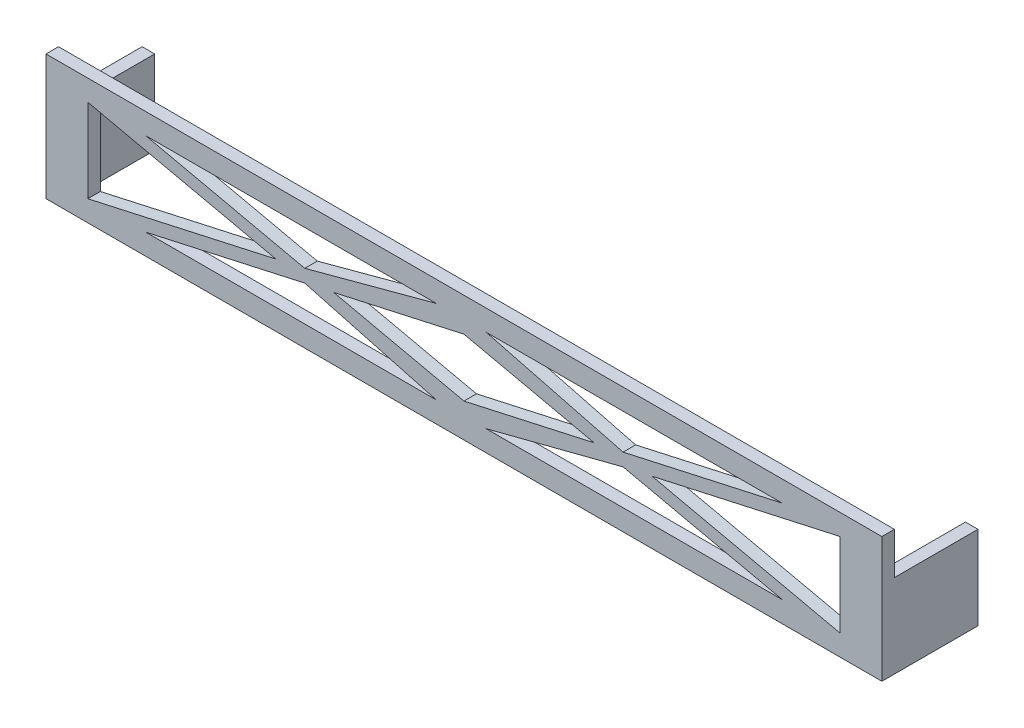
SolidWorks part; units mm, degrees
ref_plane "Alzado" through (0, 0, 0) normal (0, 0, 1) x (1, 0, 0)
ref_plane "Planta" through (0, 0, 0) normal (0, 1, 0) x (1, 0, 0)
ref_plane "Vista lateral" through (0, 0, 0) normal (1, 0, 0) x (0, 0, -1)
sketch "Croquis1" plane through (0, 0, 0) normal (0, 0, 1) x (1, 0, 0)
  line L0 (-28.1596, 43.8518) -> (-28.1596, 23.8518)
  line L1 (-218.1596, 48.8518) -> (-18.1596, 48.8518)
  line L2 (-218.1596, 48.8518) -> (-218.1596, 18.8518)
  line L3 (-218.1596, 18.8518) -> (-18.1596, 18.8518)
  line L4 (-18.1596, 48.8518) -> (-18.1596, 18.8518)
  line L9 (-208.1596, 43.8518) -> (-118.1596, 23.8518) construction
  line L10 (-118.1596, 23.8518) -> (-118.1596, 43.8518) construction
  line L11 (-118.1596, 43.8518) -> (-208.1596, 23.8518) construction
  line L12 (-208.1596, 43.8518) -> (-163.1596, 33.8518)
  line L13 (-163.1596, 33.8518) -> (-208.1596, 23.8518)
  line L14 (-194.3303, 43.8518) -> (-156.2449, 35.3884)
  line L16 (-194.3303, 23.8518) -> (-156.2449, 32.3152)
  line L18 (-156.2449, 35.3884) -> (-118.1596, 26.925) construction
  line L19 (-118.1596, 23.8518) -> (-118.1596, 28.6543) construction
  line L20 (-156.2449, 32.3152) -> (-118.1596, 40.7786) construction
  line L21 (-118.1596, 40.7786) -> (-149.3303, 33.8518)
  line L22 (-149.3303, 33.8518) -> (-118.1596, 26.925)
  line L24 (-80.0742, 32.3152) -> (-118.1596, 40.7786) construction
  line L25 (-80.0742, 35.3884) -> (-118.1596, 26.925) construction
  line L26 (-118.1596, 43.8518) -> (-28.1596, 23.8518) construction
  line L27 (-28.1596, 43.8518) -> (-118.1596, 23.8518) construction
  line L29 (-86.9889, 33.8518) -> (-118.1596, 26.925)
  line L30 (-118.1596, 40.7786) -> (-86.9889, 33.8518)
  line L32 (-41.9889, 23.8518) -> (-80.0742, 32.3152)
  line L34 (-41.9889, 43.8518) -> (-80.0742, 35.3884)
  line L35 (-73.1596, 33.8518) -> (-28.1596, 23.8518)
  line L36 (-28.1596, 43.8518) -> (-73.1596, 33.8518)
  line L38 (-208.1596, 43.8518) -> (-208.1596, 23.8518)
  line L49 (-80.0742, 32.3152) -> (-112.872, 23.8518)
  line L50 (-156.2449, 32.3152) -> (-124.7714, 23.8518)
  line L51 (-156.2449, 35.3884) -> (-124.7714, 43.8518)
  line L52 (-80.0742, 35.3884) -> (-112.872, 43.8518)
  line L53 (-194.3303, 23.8518) -> (-124.7714, 23.8518)
  line L54 (-112.872, 23.8518) -> (-41.9889, 23.8518)
  line L55 (-41.9889, 43.8518) -> (-112.872, 43.8518)
  line L56 (-124.7714, 43.8518) -> (-194.3303, 43.8518)
  dimension "D1" = 200
  dimension "D2" = 30
  dimension "D7" = 3
extrude "Saliente-Extruir1" add sketch "Croquis1" along normal blind 3
sketch "Croquis2" plane through (0, 0, 3) normal (0, 0, 1) x (1, 0, 0)
  line L0 (-218.1596, 48.8518) -> (-218.1596, 18.8518) construction
  line L1 (-218.1596, 38.8518) -> (-215.1596, 38.8518)
  line L2 (-218.1596, 38.8518) -> (-218.1596, 18.8518)
  line L3 (-218.1596, 18.8518) -> (-215.1596, 18.8518)
  line L4 (-215.1596, 38.8518) -> (-215.1596, 18.8518)
  line L5 (-218.1596, 18.8518) -> (-18.1596, 18.8518) construction
  line L6 (-118.1596, 48.8518) -> (-118.1596, 18.8518) construction
  line L7 (-18.1596, 48.8518) -> (-218.1596, 48.8518) construction
  line L8 (-21.1596, 38.8518) -> (-21.1596, 18.8518)
  line L9 (-18.1596, 18.8518) -> (-21.1596, 18.8518)
  line L10 (-18.1596, 38.8518) -> (-18.1596, 18.8518)
  line L11 (-18.1596, 38.8518) -> (-21.1596, 38.8518)
  dimension "D1" = 3
  dimension "D2" = 20
extrude "Saliente-Extruir2" add sketch "Croquis2" against normal blind 23
